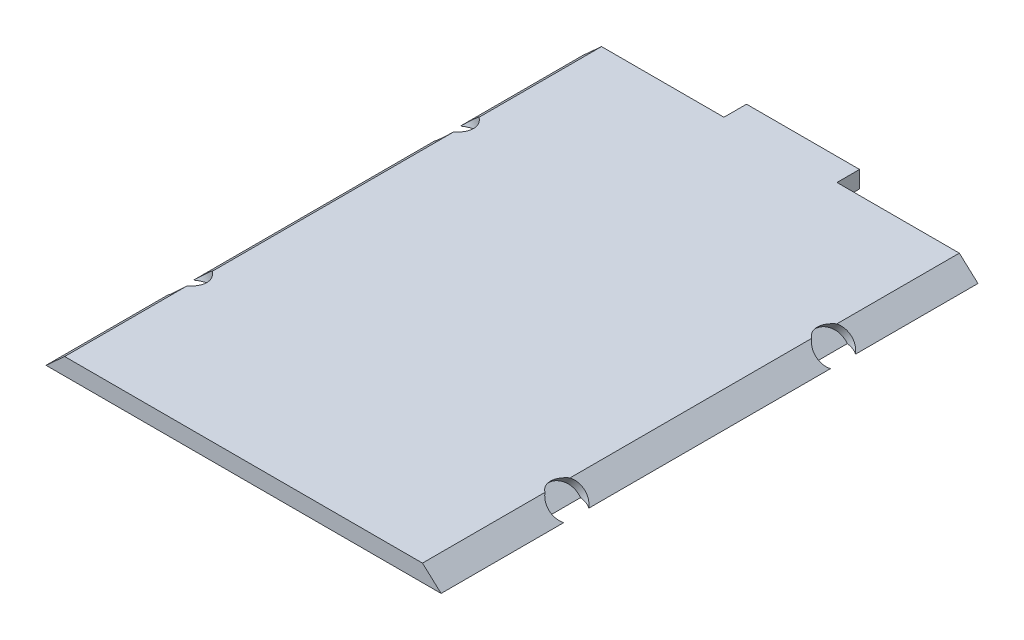
SolidWorks part; units mm, degrees
ref_plane "Front Plane" through (0, 0, 0) normal (0, 0, 1) x (1, 0, 0)
ref_plane "Top Plane" through (0, 0, 0) normal (0, 1, 0) x (1, 0, 0)
ref_plane "Right Plane" through (0, 0, 0) normal (1, 0, 0) x (0, 0, -1)
sketch "Sketch1" plane through (0, 0, 0) normal (0, 0, 1) x (1, 0, 0)
  line L0 (0, 0) -> (0, 44.45) construction
  line L1 (-40.2039, 5.9378) -> (40.2039, 5.9378)
  line L2 (-44.399, 2.1278) -> (44.399, 2.1278)
  line L3 (-40.2039, 5.9378) -> (-44.399, 2.1278)
  line L4 (40.2039, 5.9378) -> (44.399, 2.1278)
  arc A0 (44.399, 2.1278) -> (-44.399, 2.1278) centre (0, 0) ccw construction
  arc A1 (40.2039, 5.9378) -> (-40.2039, 5.9378) centre (0, 0) ccw construction
  dimension "D1" = 88.9
  dimension "D2" = 3.81
  dimension "D3" = 3.81
extrude "Boss-Extrude1" add sketch "Sketch1" along normal blind 120.65
sketch "Sketch2" plane through (0, 2.1278, 0) normal (0, -1, 0) x (1, 0, 0)
  line L0 (-44.399, 0) -> (44.399, 0) construction
  line L1 (-12.7, 0) -> (12.7, 0)
  line L2 (-12.7, 0) -> (-12.7, -5.08)
  line L3 (-12.7, -5.08) -> (12.7, -5.08)
  line L4 (12.7, 0) -> (12.7, -5.08)
  line L5 (0, 0) -> (0, -5.08) construction
  line L6 (0, 0) -> (0, 120.65) construction
  line L7 (-44.399, 120.65) -> (44.399, 120.65) construction
  dimension "D1" = 25.4
  dimension "D2" = 5.08
  dimension "D3" = 0
extrude "Boss-Extrude2" add sketch "Sketch2" against normal blind 3.81
sketch "Sketch3" plane through (-21.1272, 23.263, 0) normal (-0.6723, 0.7403, 0) x (0.7403, 0.6723, 0)
  line L0 (-28.6033, 0) -> (-28.6033, -120.65) construction
  line L1 (-25.7698, 0) -> (-31.4368, 0) construction
  line L2 (-25.7698, -60.325) -> (-31.4368, -60.325) construction
  line L3 (-25.7698, -120.65) -> (-25.7698, 0) construction
  line L4 (-31.4368, -120.65) -> (-31.4368, 0) construction
  circle A0 centre (-28.6033, -30.353) radius 4
  circle A1 centre (-28.6033, -90.297) radius 4
  point P12 (-28.6033, -60.325)
  dimension "D1" = 8
  dimension "D2" = 29.972
  dimension "D3" = 120.65
extrude "Cut-Extrude1" cut sketch "Sketch3" against normal blind 2
sketch "Sketch4" plane through (21.1272, 23.263, 0) normal (0.6723, 0.7403, 0) x (0.7403, -0.6723, 0)
  line L0 (28.6033, -120.65) -> (28.6033, 0) construction
  line L1 (31.4368, -120.65) -> (25.7698, -120.65) construction
  line L2 (25.7698, -60.325) -> (31.4368, -60.325) construction
  line L3 (25.7698, -120.65) -> (25.7698, 0) construction
  line L4 (31.4368, -120.65) -> (31.4368, 0) construction
  circle A0 centre (28.6033, -90.297) radius 4
  circle A1 centre (28.6033, -30.353) radius 4
  point P13 (28.6033, -60.325)
  dimension "D1" = 8
  dimension "D2" = 29.972
  dimension "D3" = 120.65
extrude "Cut-Extrude2" cut sketch "Sketch4" against normal blind 2
